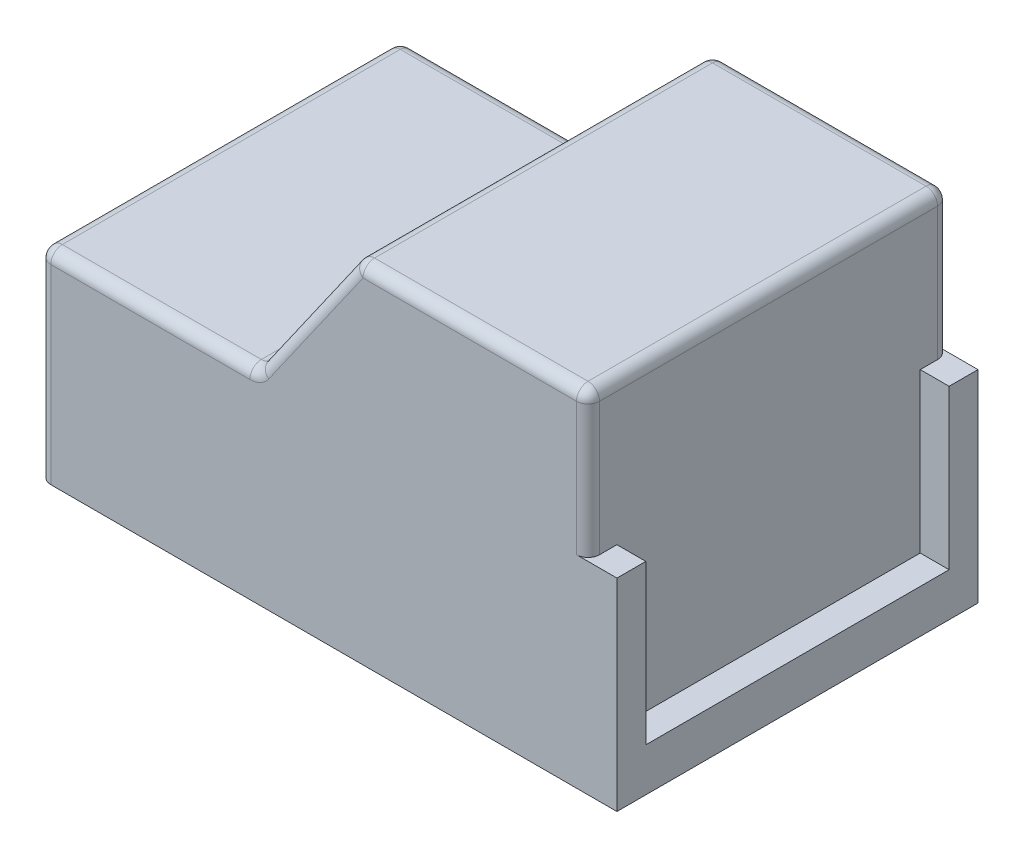
SolidWorks part; units mm, degrees
material "PC High Viscosity"
ref_plane "Front Plane" through (0, 0, 0) normal (0, 0, 1) x (1, 0, 0)
ref_plane "Top Plane" through (0, 0, 0) normal (0, 1, 0) x (1, 0, 0)
ref_plane "Right Plane" through (0, 0, 0) normal (1, 0, 0) x (0, 0, -1)
sketch "Sketch1" plane through (0, 0, 0) normal (0, 0, 1) x (1, 0, 0)
  line L0 (-406.4, 88.9) -> (-406.4, -88.9)
  line L1 (-406.4, -88.9) -> (101.6, -88.9)
  line L2 (101.6, -88.9) -> (101.6, 88.9)
  line L3 (101.6, 88.9) -> (76.2, 88.9)
  line L4 (76.2, 88.9) -> (76.2, 215.9)
  line L5 (76.2, 215.9) -> (-126.9736, 215.9)
  line L6 (-126.9736, 215.9) -> (-215.9, 88.9)
  line L7 (-215.9, 88.9) -> (-406.4, 88.9)
  dimension "D1" = 508
  dimension "D2" = 190.5
  dimension "D3" = 177.8
  dimension "D4" = 177.8
  dimension "D6" = 127
  dimension "D7" = 55
extrude "Boss-Extrude1" add sketch "Sketch1" along normal mid plane 317.5
sketch "Sketch2" plane through (0, 88.9, 0) normal (0, 1, 0) x (1, 0, 0)
  line L0 (0, 0) -> (457.4515, 0) construction
  line L1 (76.2, -133.35) -> (101.6, -133.35)
  line L2 (76.2, -133.35) -> (76.2, 133.35)
  line L3 (76.2, 133.35) -> (101.6, 133.35)
  line L4 (101.6, -133.35) -> (101.6, 133.35)
  line L5 (76.2, -133.35) -> (101.6, 133.35) construction
  line L6 (76.2, 133.35) -> (101.6, -133.35) construction
  line L7 (101.6, 158.75) -> (76.2, 158.75) construction
  line L8 (101.6, -158.75) -> (101.6, 158.75) construction
  line L9 (76.2, -158.75) -> (76.2, 158.75) construction
  line L10 (101.6, -158.75) -> (76.2, -158.75) construction
  point P0 (88.9, 0)
  dimension "D1" = 25.4
  dimension "D2" = 25.4
  dimension "D3" = 25.4
  dimension "D4" = 25.4
extrude "Cut-Extrude1" cut sketch "Sketch2" against normal blind 139.7
fillet "Fillet1" radius 10.16 14 edges at (-171.4368, 152.4, 158.75) (-171.4368, 152.4, -158.75) (-215.9, 88.9, 0) (-311.15, 88.9, 158.75) (-406.4, 88.9, 0) (-311.15, 88.9, -158.75) (76.2, 152.4, -158.75) (76.2, 152.4, 158.75) (-25.3868, 215.9, -158.75) (-25.3868, 215.9, 158.75) (76.2, 215.9, 0) (-126.9736, 215.9, 0) (-406.4, 0, -158.75) (-406.4, 0, 158.75)
sketch "Sketch3" plane through (0, -88.9, 0) normal (0, -1, 0) x (1, 0, 0)
  circle A0 centre (0, 0) radius 20
